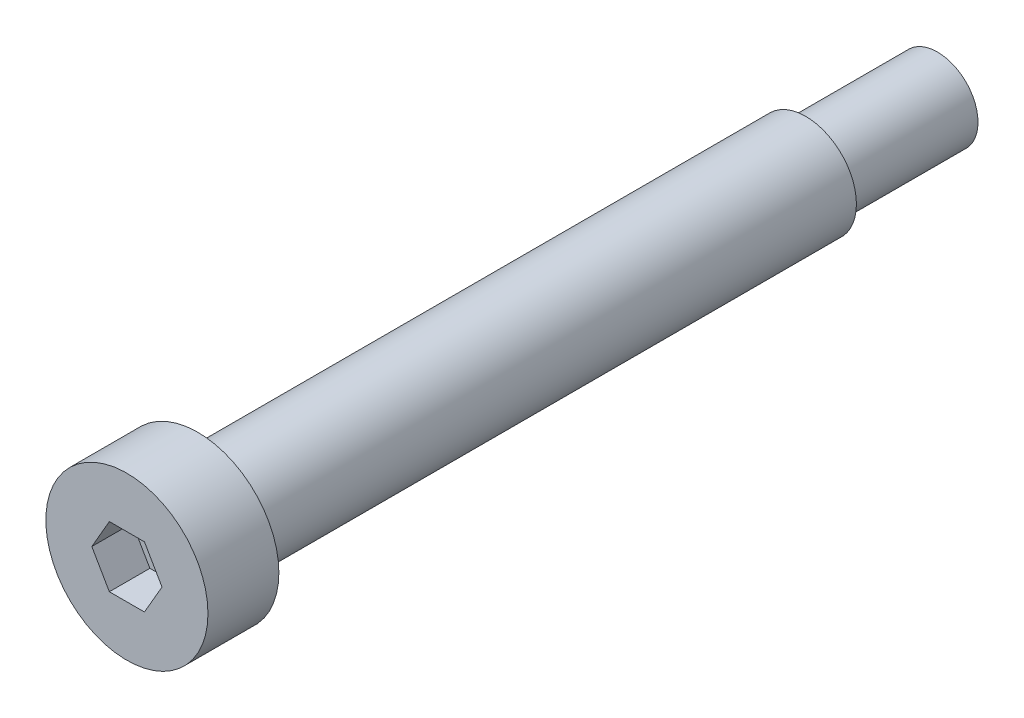
SolidWorks part; units mm, degrees
ref_plane "Front Plane" through (0, 0, 0) normal (0, 0, 1) x (1, 0, 0)
ref_plane "Top Plane" through (0, 0, 0) normal (0, 1, 0) x (1, 0, 0)
ref_plane "Right Plane" through (0, 0, 0) normal (1, 0, 0) x (0, 0, -1)
sketch "Sketch1" plane through (0, 0, 0) normal (0, 0, 1) x (1, 0, 0)
  circle A0 centre (0, 0) radius 2
extrude "Thread" add sketch "Sketch1" along normal blind 6.5
ref_plane "Plane_z6_5" through (0, 0, 6.5) normal (0, 0, 1) x (1, 0, 0)
sketch "Sketch2" plane through (0, 0, 6.5) normal (0, 0, 1) x (1, 0, 0)
  circle A0 centre (0, 0) radius 2.5
extrude "Shoulder" add sketch "Sketch2" along normal blind 30
ref_plane "Plane_z36_5" through (0, 0, 36.5) normal (0, 0, 1) x (1, 0, 0)
sketch "Sketch3" plane through (0, 0, 36.5) normal (0, 0, 1) x (1, 0, 0)
  circle A0 centre (0, 0) radius 4
extrude "Head" add sketch "Sketch3" along normal blind 3.5
ref_plane "Plane_z38" through (0, 0, 38) normal (0, 0, 1) x (1, 0, 0)
sketch "Sketch4" plane through (0, 0, 38) normal (0, 0, 1) x (1, 0, 0)
  line L0 (1.7321, 0) -> (0.866, 1.5)
  line L1 (0.866, 1.5) -> (-0.866, 1.5)
  line L2 (-0.866, 1.5) -> (-1.7321, 0)
  line L3 (-1.7321, 0) -> (-0.866, -1.5)
  line L4 (-0.866, -1.5) -> (0.866, -1.5)
  line L5 (0.866, -1.5) -> (1.7321, 0)
extrude "Socket" cut sketch "Sketch4" along normal blind 2
